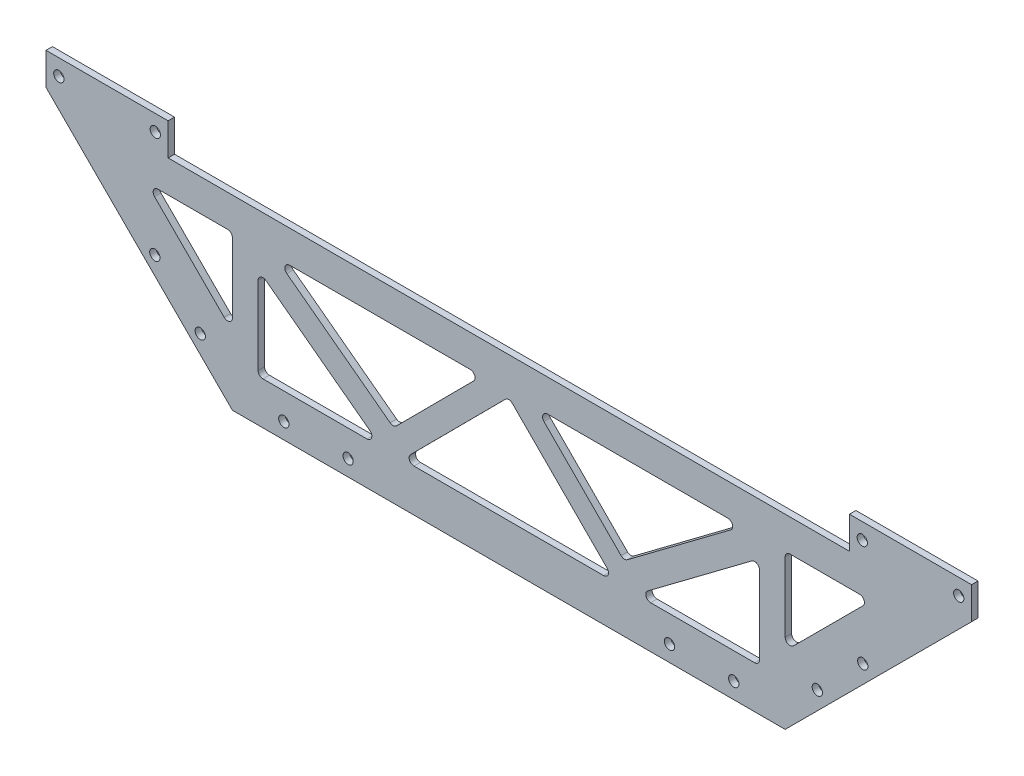
SolidWorks part; units mm, degrees
material "Thornel Mat VMA"
ref_plane "前视基准面" through (0, 0, 0) normal (0, 0, 1) x (1, 0, 0)
ref_plane "上视基准面" through (0, 0, 0) normal (0, 1, 0) x (1, 0, 0)
ref_plane "右视基准面" through (0, 0, 0) normal (1, 0, 0) x (0, 0, -1)
sketch "草图1" plane through (0, 0, 0) normal (0, 0, 1) x (1, 0, 0)
  line L0 (-106, 30) -> (-106, 0)
  line L1 (-106, 0) -> (106, 0)
  line L2 (106, 0) -> (106, 30)
  line L3 (-106, 30) -> (-144, 30)
  line L5 (-86, -58) -> (86, -58)
  line L7 (144, 30) -> (106, 30)
  line L8 (0, 0) -> (0, -58) construction
  line L9 (-140, 25) -> (-110, 25) construction
  line L10 (-140, 25) -> (-140, 5) construction
  line L11 (-140, 5) -> (-110, 5) construction
  line L12 (-110, 25) -> (-110, 5) construction
  line L13 (110, 25) -> (110, 5) construction
  line L14 (140, 5) -> (110, 5) construction
  line L15 (140, 25) -> (140, 5) construction
  line L16 (140, 25) -> (110, 25) construction
  line L17 (-70, -53) -> (-50, -53) construction
  line L18 (70, -53) -> (50, -53) construction
  line L19 (-144, 30) -> (-144, 0)
  line L20 (-144, 0) -> (-86, -58)
  line L21 (86, -58) -> (144, 0)
  line L22 (144, 0) -> (144, 30)
  circle A0 centre (-140, 25) radius 1.6
  circle A1 centre (-110, 25) radius 1.6
  circle A2 centre (-110, 5) radius 1.6
  circle A3 centre (-140, 5) radius 1.6
  circle A4 centre (140, 5) radius 1.6
  circle A5 centre (110, 5) radius 1.6
  circle A6 centre (110, 25) radius 1.6
  circle A7 centre (140, 25) radius 1.6
  circle A8 centre (-70, -53) radius 1.6
  circle A9 centre (-50, -53) radius 1.6
  circle A10 centre (50, -53) radius 1.6
  circle A11 centre (70, -53) radius 1.6
  point P4 (0, 0)
  dimension "D5" = 3.2
  dimension "D10" = 3.2
  dimension "D1" = 30
  dimension "D2" = 212
  dimension "D3" = 58
  dimension "D4" = 38
  dimension "D6" = 5
  dimension "D7" = 5
  dimension "D8" = 4
  dimension "D9" = 4
  dimension "D11" = 20
  dimension "D12" = 50
  dimension "D13" = 5
  dimension "D14" = 45
extrude "凸台-拉伸1" add sketch "草图1" along normal blind 2
sketch "草图2" plane through (0, 0, 2) normal (0, 0, 1) x (1, 0, 0)
  line L0 (-110.1421, -28.201) -> (-96, -42.3431) construction
  line L1 (0, 0) -> (0, -58) construction
  line L2 (-86, -58) -> (86, -58) construction
  line L3 (-144, 0) -> (-86, -58) construction
  line L4 (110.1421, -28.201) -> (96, -42.3431) construction
  circle A0 centre (-110.1421, -28.201) radius 1.6
  circle A1 centre (-96, -42.3431) radius 1.6
  circle A2 centre (96, -42.3431) radius 1.6
  circle A3 centre (110.1421, -28.201) radius 1.6
  dimension "D3" = 3.2
  dimension "D1" = 4
  dimension "D2" = 20
  dimension "D4" = 10
extrude "切除-拉伸1" cut sketch "草图2" against normal through all
sketch "草图3" plane through (0, 0, 2) normal (0, 0, 1) x (1, 0, 0)
  line L0 (144, 0) -> (144, 30) construction
  line L1 (-144, 30) -> (144, 30)
  line L2 (-144, 30) -> (-144, 10)
  line L3 (-144, 10) -> (144, 10)
  line L4 (144, 30) -> (144, 10)
  circle A0 centre (140, 5) radius 1.6 construction
  dimension "D1" = 5
extrude "切除-拉伸2" cut sketch "草图3" against normal through all
sketch "草图4" plane through (0, 0, 2) normal (0, 0, 1) x (1, 0, 0)
  line L0 (-110.2261, -12.5607) -> (-88.5607, -34.2261)
  line L1 (-86, -33.1655) -> (-86, -11.5)
  line L2 (-87.5, -10) -> (-109.1655, -10)
  line L3 (106, 0) -> (-106, 0) construction
  line L4 (-144, 0) -> (-86, -58) construction
  line L5 (0, 0) -> (0, -58) construction
  line L6 (-86, -58) -> (86, -58) construction
  line L10 (-78, -19) -> (-78, -43.2868)
  line L11 (-76.5, -44.7868) -> (-44.1176, -44.7868)
  line L12 (-43.2176, -42.0868) -> (-75.6, -17.8)
  line L13 (-68.1667, -10) -> (-12, -10)
  line L14 (-10.9366, -12.5579) -> (-34.9366, -36.6829)
  line L15 (-36.9, -36.825) -> (-69.0667, -12.7)
  line L20 (36.9, -36.825) -> (69.0667, -12.7)
  line L21 (10.9366, -12.5579) -> (34.9366, -36.6829)
  line L22 (68.1667, -10) -> (12, -10)
  line L23 (43.2176, -42.0868) -> (75.6, -17.8)
  line L24 (76.5, -44.7868) -> (44.1176, -44.7868)
  line L25 (78, -19) -> (78, -43.2868)
  line L26 (87.5, -10) -> (109.1655, -10)
  line L27 (86, -33.1655) -> (86, -11.5)
  line L28 (110.2261, -12.5607) -> (88.5607, -34.2261)
  line L29 (-30.58, -42.2289) -> (-1.0634, -12.5586)
  line L30 (-29.5166, -44.7868) -> (29.5166, -44.7868)
  line L31 (30.58, -42.2289) -> (1.0634, -12.5586)
  arc A4 (-12, -10) -> (-10.9366, -12.5579) centre (-12, -11.5) cw
  arc A5 (-34.9366, -36.6829) -> (-36.9, -36.825) centre (-36, -35.625) cw
  arc A6 (-68.1667, -10) -> (-69.0667, -12.7) centre (-68.1667, -11.5) ccw
  arc A7 (-44.1176, -44.7868) -> (-43.2176, -42.0868) centre (-44.1176, -43.2868) ccw
  arc A8 (-78, -43.2868) -> (-76.5, -44.7868) centre (-76.5, -43.2868) ccw
  arc A9 (-78, -19) -> (-75.6, -17.8) centre (-76.5, -19) cw
  arc A10 (-88.5607, -34.2261) -> (-86, -33.1655) centre (-87.5, -33.1655) ccw
  arc A11 (-86, -11.5) -> (-87.5, -10) centre (-87.5, -11.5) ccw
  arc A12 (-110.2261, -12.5607) -> (-109.1655, -10) centre (-109.1655, -11.5) cw
  arc A13 (110.2261, -12.5607) -> (109.1655, -10) centre (109.1655, -11.5) ccw
  arc A14 (86, -11.5) -> (87.5, -10) centre (87.5, -11.5) cw
  arc A15 (88.5607, -34.2261) -> (86, -33.1655) centre (87.5, -33.1655) cw
  arc A16 (78, -19) -> (75.6, -17.8) centre (76.5, -19) ccw
  arc A17 (78, -43.2868) -> (76.5, -44.7868) centre (76.5, -43.2868) cw
  arc A18 (44.1176, -44.7868) -> (43.2176, -42.0868) centre (44.1176, -43.2868) cw
  arc A19 (68.1667, -10) -> (69.0667, -12.7) centre (68.1667, -11.5) cw
  arc A20 (34.9366, -36.6829) -> (36.9, -36.825) centre (36, -35.625) ccw
  arc A21 (12, -10) -> (10.9366, -12.5579) centre (12, -11.5) ccw
  arc A22 (30.58, -42.2289) -> (29.5166, -44.7868) centre (29.5166, -43.2868) cw
  arc A23 (-30.58, -42.2289) -> (-29.5166, -44.7868) centre (-29.5166, -43.2868) ccw
  arc A24 (-1.0634, -12.5586) -> (1.0634, -12.5586) centre (0, -13.6165) cw
  point P23 (33.1246, -44.7868)
  point P27 (-33.1246, -44.7868)
  point P31 (0, -11.4897)
  point P46 (-72.6667, -10)
  point P51 (-78, -44.7868)
  point P54 (-78, -16)
  point P59 (-86, -10)
  point P89 (86, -10)
  point P90 (78, -16)
  point P91 (78, -44.7868)
  point P92 (72.6667, -10)
  dimension "D7" = 1.5
  dimension "D10" = 1.5
  dimension "D1" = 10
  dimension "D2" = 15
  dimension "D3" = 8
  dimension "D4" = 8
  dimension "D5" = 6
  dimension "D6" = 12
  dimension "D8" = 36
  dimension "D9" = 7
extrude "切除-拉伸3" cut sketch "草图4" against normal through all and the other way through all
